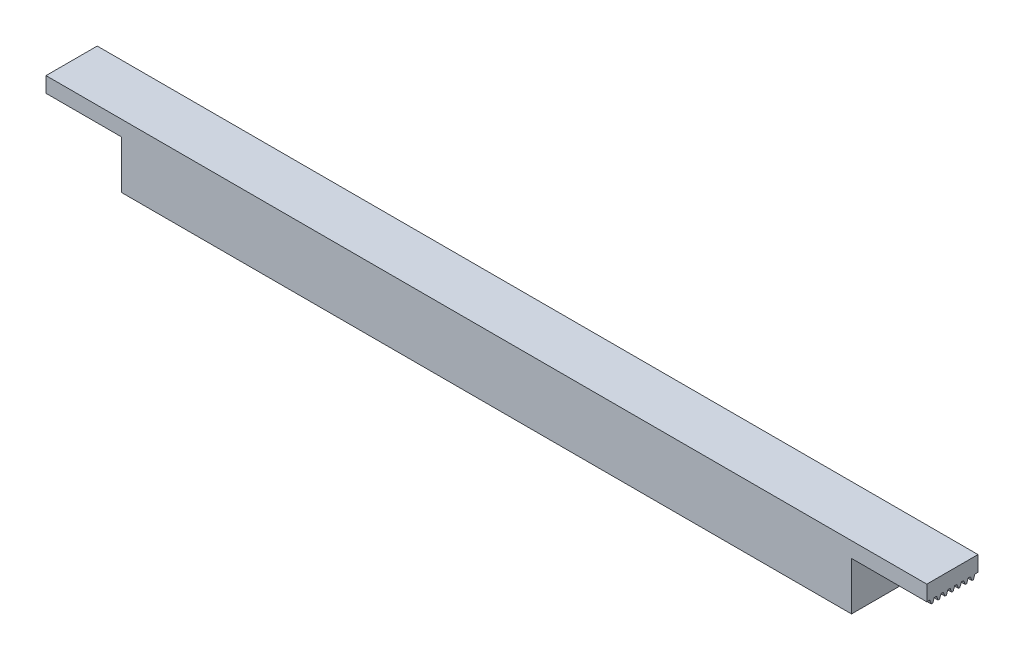
SolidWorks part; units mm, degrees
ref_plane "Front" through (0, 0, 0) normal (0, 0, 1) x (1, 0, 0)
ref_plane "Top" through (0, 0, 0) normal (0, 1, 0) x (1, 0, 0)
ref_plane "Right" through (0, 0, 0) normal (1, 0, 0) x (0, 0, -1)
sketch "Sketch1" plane through (0, 0, 0) normal (0, 1, 0) x (1, 0, 0)
  line L0 (-43, 0) -> (43, 0) construction
  line L1 (-43, 2.5) -> (43, 2.5)
  line L2 (-43, 2.5) -> (-43, -2.5)
  line L3 (-43, -2.5) -> (43, -2.5)
  line L4 (43, 2.5) -> (43, -2.5)
  line L5 (0, 2.5) -> (0, -2.5) construction
  dimension "D1" = 86
  dimension "D2" = 5
extrude "Boss-Extrude1" add sketch "Sketch1" along normal blind 6.2
sketch "Sketch2" plane through (0, 0, 2.5) normal (0, 0, 1) x (1, 0, 0)
  line L0 (0, 0) -> (0, 23.2403) construction
  line L1 (-43, 0) -> (43, 0) construction
  line L3 (43, 0) -> (35.65, 0)
  line L4 (43, 0) -> (43, 4.7)
  line L5 (43, 4.7) -> (35.65, 4.7)
  line L6 (35.65, 0) -> (35.65, 4.7)
  dimension "D1" = 35.65
  dimension "D2" = 4.7
extrude "Cut-Extrude1" cut sketch "Sketch2" against normal blind 10
mirror "Mirror1" about plane through (0, 0, 0) normal (1, 0, 0) of "Cut-Extrude1"
sketch "Sketch3" plane through (0, 0, 0) normal (0, -1, 0) x (1, 0, 0)
  line L0 (0, 2.5) -> (0, 26.6311) construction
  line L1 (-35.65, 2.5) -> (35.65, 2.5) construction
  line L2 (-43, 0) -> (43, 0) construction
  line L3 (-43, -2.5) -> (-43, 2.5) construction
  line L4 (43, -2.5) -> (43, 2.5) construction
  circle A0 centre (-3, 0) radius 0.5
  circle A1 centre (-6, 0) radius 0.5
  dimension "D1" = 1
  dimension "D3" = 1
  dimension "D2" = 3
  dimension "D4" = 3
extrude "First hold-down cylinders" add sketch "Sketch3" along normal blind 1
pattern_linear "LPattern1" count 5 spacing 9 along (1, 0, 0) count 4 spacing 9 along (-1, 0, 0) of "First hold-down cylinders"
sketch "Sketch5" plane through (0, 0, -2.5) normal (0, 0, -1) x (-1, 0, 0)
  line L0 (-43, 6.2) -> (43, 6.2) construction
  line L1 (43, 4.7) -> (35.65, 4.7)
  line L2 (43, 4.7) -> (43, 6.2)
  line L3 (43, 6.2) -> (35.65, 6.2)
  line L4 (35.65, 4.7) -> (35.65, 6.2)
ref_plane "long mirror plane" through (0, 0, 0) normal (0, 0, -1) x (-1, 0, 0)
sketch "Sketch4" plane through (43, 0, 0) normal (1, 0, 0) x (0, 0, -1)
  line L0 (0, 4.7) -> (0, -1.3359) construction
  line L1 (2.5, 4.7) -> (-2.5, 4.7) construction
  line L10 (0, 4.7) -> (-3.1142, 4.7) construction
  line L11 (0.2206, 4.7) -> (-0.2206, 4.7)
  line L12 (0.075, 4.3) -> (0.2206, 4.7)
  line L13 (-0.075, 4.3) -> (0.075, 4.3)
  line L14 (-0.2206, 4.7) -> (-0.075, 4.3)
  line L15 (2.5, 4.7) -> (-2.5, 4.7) construction
  point P5 (0, 4.7)
  point P8 (0, 4.3)
  dimension "D1" = 0.4
  dimension "D2" = 40
  dimension "D4" = 0.15
extrude "First Ridge" add sketch "Sketch4" against normal blind 7.35
pattern_linear "Rack Left Pattern" count 4 spacing 0.6629 along (0, 0, 1) count 4 spacing 0.66 along (0, 0, -1) of "First Ridge"
mirror "Mirror2" about plane through (0, 0, 0) normal (1, 0, 0) of "Rack Left Pattern", "First Ridge"
